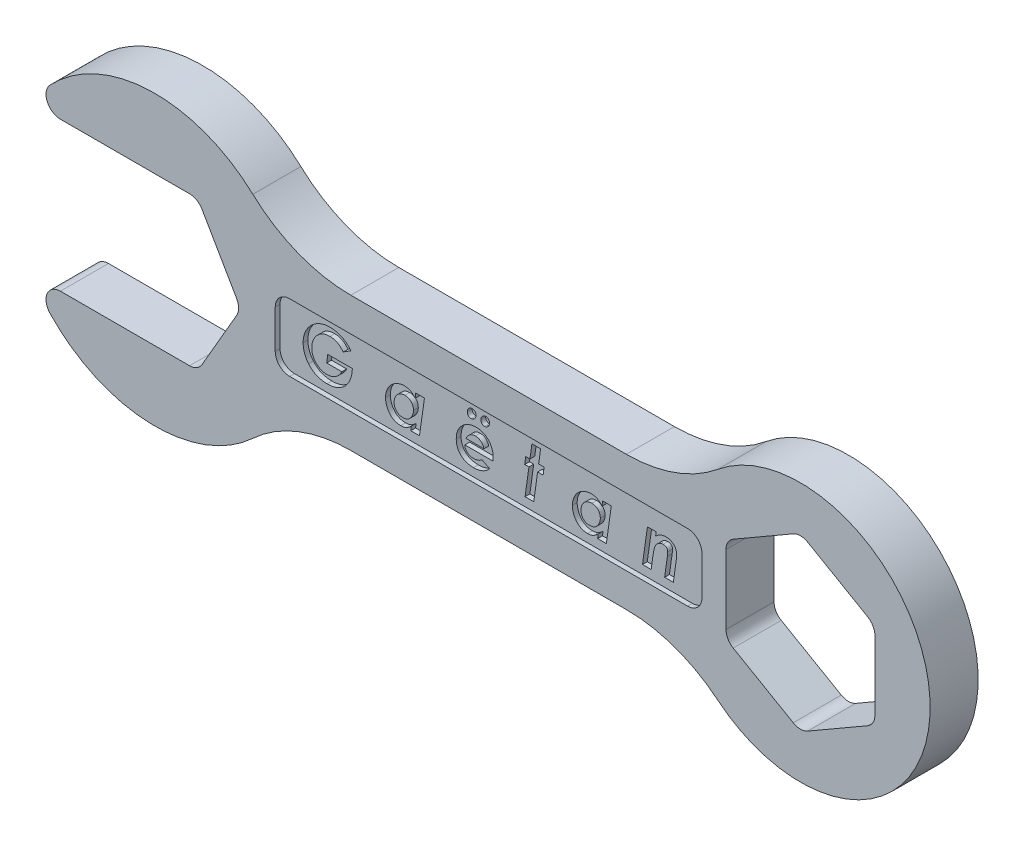
SolidWorks part; units mm, degrees
ref_plane "Plan de face" through (0, 0, 0) normal (0, 0, 1) x (1, 0, 0)
ref_plane "Plan de dessus" through (0, 0, 0) normal (0, 1, 0) x (1, 0, 0)
ref_plane "Plan de droite" through (0, 0, 0) normal (1, 0, 0) x (0, 0, -1)
sketch "Esquisse1" plane through (0, 0, 0) normal (0, 0, 1) x (1, 0, 0)
  line L1 (15.5, 8.9489) -> (0, 17.8979)
  line L2 (0, 17.8979) -> (-15.5, 8.9489)
  line L3 (-15.5, 8.9489) -> (-15.5, -8.9489)
  line L4 (-15.5, -8.9489) -> (0, -17.8979)
  line L5 (0, -17.8979) -> (15.5, -8.9489)
  line L6 (15.5, -8.9489) -> (15.5, 8.9489)
  circle A0 centre (0, 0) radius 15.5 construction
  circle A1 centre (0, 0) radius 27
  dimension "D2" = 54
  dimension "D1" = 31
extrude "Boss.-Extru.1" add sketch "Esquisse1" along normal blind 10
sketch "Esquisse2" plane through (0, 0, 10) normal (0, 0, 1) x (1, 0, 0)
  line L0 (-15.5, -8.9489) -> (-15.5, -14)
  line L1 (-15.5, -14) -> (-115.5, -14)
  line L2 (-115.5, -14) -> (-115.5, 14)
  line L3 (-115.5, 0) -> (0, 0) construction
  line L4 (-15.5, 14) -> (-115.5, 14)
  line L5 (-15.5, 8.9489) -> (-15.5, 14)
  line L6 (-15.5, -8.9489) -> (-15.5, 8.9489)
  dimension "D1" = 28
  dimension "D2" = 100
extrude "Boss.-Extru.2" add sketch "Esquisse2" against normal up to vertex (10 mm away) up to point (-15.5, 8.9489, 0)
sketch "Esquisse3" plane through (0, 0, 10) normal (0, 0, 1) x (1, 0, 0)
  line L0 (-116.5, 0) -> (-115.5, 0) construction
  line L1 (-125.4489, -15.5) -> (-116.5, 0)
  line L2 (-116.5, 0) -> (-125.4489, 15.5)
  line L3 (-125.4489, 15.5) -> (-143.3468, 15.5)
  line L4 (-143.3468, 15.5) -> (-152.2957, 0)
  line L5 (-152.2957, 0) -> (-143.3468, -15.5)
  line L6 (-143.3468, -15.5) -> (-125.4489, -15.5)
  line L8 (-115.5, 14) -> (-115.5, -14) construction
  circle A0 centre (-134.3979, 0) radius 15.5 construction
  circle A1 centre (-134.3979, 0) radius 30
  dimension "D3" = 60
  dimension "D1" = 31
  dimension "D2" = 1
extrude "Boss.-Extru.3" add sketch "Esquisse3" against normal up to vertex (10 mm away)
sketch "Esquisse4" plane through (0, 0, 10) normal (0, 0, 1) x (1, 0, 0)
  line L0 (-143.3468, -15.5) -> (-160.0835, -15.5)
  line L1 (-143.3468, -15.5) -> (-125.4489, -15.5) construction
  line L2 (-143.3468, 15.5) -> (-160.0835, 15.5)
  line L3 (-125.4489, 15.5) -> (-143.3468, 15.5) construction
  line L4 (-143.3468, 15.5) -> (-143.3468, -15.5)
  arc A0 (-107.8649, 14) -> (-107.8649, -14) centre (-134.3979, 0) ccw construction
  arc A1 (-160.0835, -15.5) -> (-160.0835, 15.5) centre (-134.3979, 0) cw
extrude "Enlèv. mat.-Extru.1" cut sketch "Esquisse4" against normal through all both and the other way through all
fillet "Congé1" radius 3 2 edges
fillet "Congé2" radius 30 4 edges at (-23.0868, 14, 5) (-23.0868, -14, 5) (-107.8649, 14, 5) (-107.8649, -14, 5)
fillet "Congé3" radius 3 9 edges at (0, -17.8979, 5) (-15.5, -8.9489, 5) (-15.5, 8.9489, 5) (0, 17.8979, 5) (15.5, 8.9489, 5) (15.5, -8.9489, 5) (-125.4489, -15.5, 5) (-116.5, 0, 5) (-125.4489, 15.5, 5)
sketch "Esquisse5" plane through (0, 0, 10) normal (0, 0, 1) x (1, 0, 0)
  line L0 (-36.2353, 14) -> (-93.6057, 14) construction
  line L1 (-109.341, 7) -> (-20.5, 7)
  line L2 (-109.341, 7) -> (-109.341, -7)
  line L3 (-109.341, -7) -> (-20.5, -7)
  line L4 (-20.5, 7) -> (-20.5, -7)
  line L5 (-20.5, 0) -> (-15.5, 0) construction
  line L6 (-15.5, 7.2169) -> (-15.5, -7.2169) construction
  line L7 (-64.9205, -7) -> (-64.9205, -14) construction
  line L8 (-93.6057, -14) -> (-36.2353, -14) construction
  dimension "D1" = 7
  dimension "D2" = 5
extrude "Enlèv. mat.-Extru.2" cut sketch "Esquisse5" against normal blind 1
fillet "Congé4" radius 3 4 edges at (-20.5, -7, 9.5) (-20.5, 7, 9.5) (-109.341, 7, 9.5) (-109.341, -7, 9.5)
sketch "Esquisse6" plane through (0, 0, 9) normal (0, 0, 1) x (1, 0, 0)
  line L0 (-109.341, 0) -> (-20.5, 0) construction
  line L1 (-109.341, 4) -> (-109.341, -4) construction
  line L2 (-20.5, -4) -> (-20.5, 4) construction
  line L3 (-64.9205, -7) -> (-64.9205, 7) construction
  line L4 (-106.341, -7) -> (-23.5, -7) construction
  line L5 (-23.5, 7) -> (-106.341, 7) construction
  text T0 "<i>Gaëtan</i>" font "Century Gothic" height 10
extrude "Enlèv. mat.-Extru.3" cut sketch "Esquisse6" against normal blind 1
